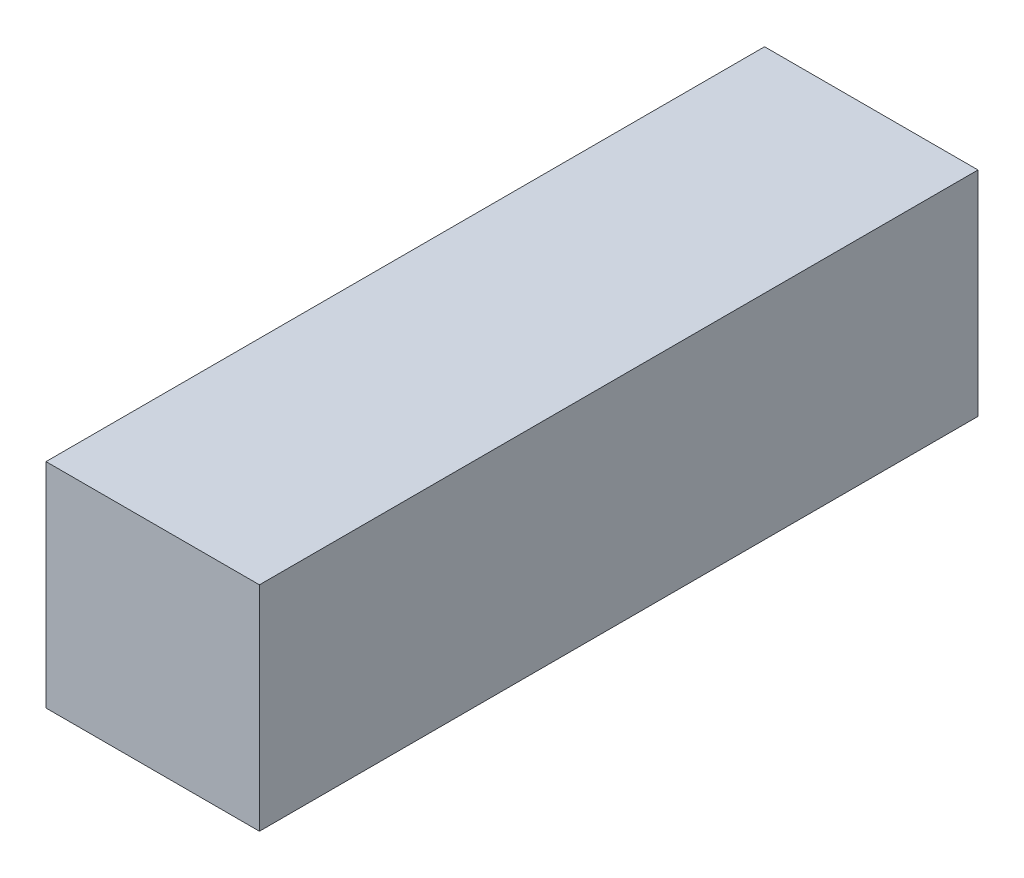
SolidWorks part; units mm, degrees
ref_plane "Front" through (0, 0, 0) normal (0, 0, 1) x (1, 0, 0)
ref_plane "Top" through (0, 0, 0) normal (0, 1, 0) x (1, 0, 0)
ref_plane "Right" through (0, 0, 0) normal (1, 0, 0) x (0, 0, -1)
sketch "Sketch1" plane through (0, 0, 0) normal (0, 0, 1) x (1, 0, 0)
  line L1 (-15, -15) -> (15, -15)
  line L2 (-15, -15) -> (-15, 15)
  line L3 (-15, 15) -> (15, 15)
  line L4 (15, -15) -> (15, 15)
  line L5 (-15, -15) -> (15, 15) construction
  line L6 (-15, 15) -> (15, -15) construction
  point P0 (0, 0)
  dimension "D1" = 30
extrude "Boss-Extrude1" add sketch "Sketch1" along normal blind 101
